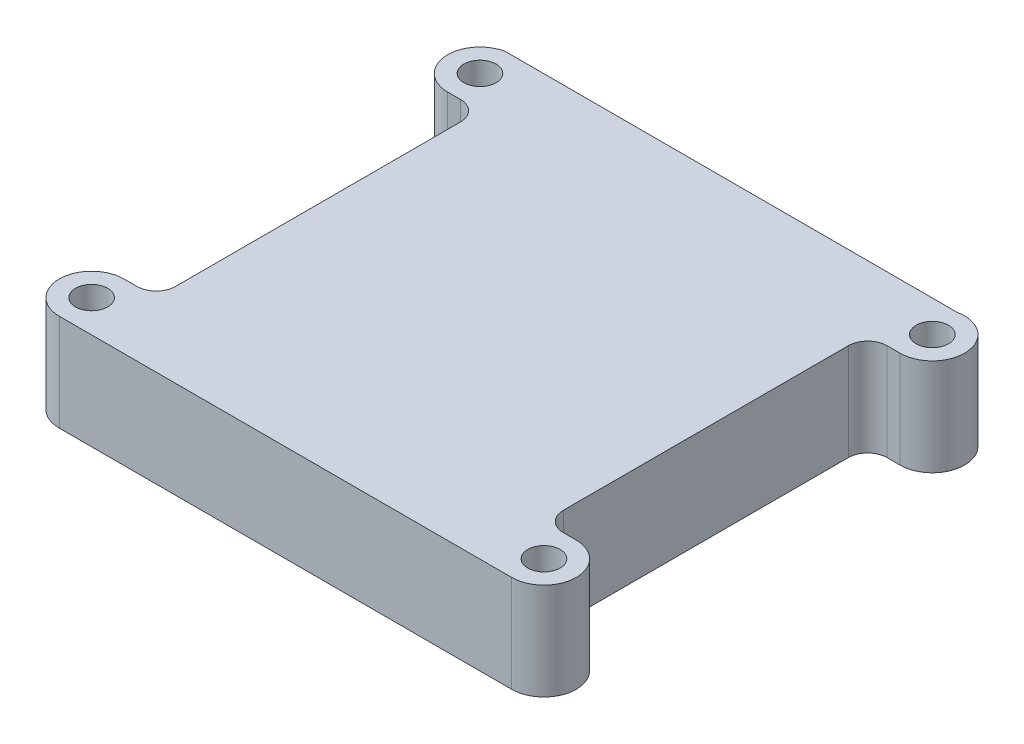
SolidWorks part; units mm, degrees
ref_plane "Front Plane" through (0, 0, 0) normal (0, 0, 1) x (1, 0, 0)
ref_plane "Top Plane" through (0, 0, 0) normal (0, 1, 0) x (1, 0, 0)
ref_plane "Right Plane" through (0, 0, 0) normal (1, 0, 0) x (0, 0, -1)
sketch "Sketch1" plane through (0, 0, 0) normal (0, 1, 0) x (1, 0, 0)
  line L0 (-35, 30.099) -> (35, 30.099) construction
  line L1 (-30, -35) -> (30, -35)
  line L2 (-30, -22) -> (-30, 22.099)
  line L3 (-30, 35) -> (30, 35)
  line L5 (-30, -35) -> (30, 35) construction
  line L6 (-30, 35) -> (30, -35) construction
  line L7 (-35.9898, 35) -> (-30, 35)
  line L8 (-35, 25.099) -> (-33, 25.099)
  line L9 (-35, -30) -> (35, -30) construction
  line L10 (-35, -25) -> (-33, -25)
  line L11 (-35, -35) -> (-30, -35)
  line L12 (33, 25.099) -> (35, 25.099)
  line L13 (30, 35) -> (34.0102, 35)
  line L14 (33, -25) -> (35, -25)
  line L15 (30, -35) -> (35, -35)
  line L16 (30, -22) -> (30, 22.099)
  arc A0 (-35.9898, 35) -> (-35, 25.099) centre (-35, 30.099) ccw
  arc A1 (35, 25.099) -> (34.0102, 35) centre (35, 30.099) ccw
  arc A2 (-35, -25) -> (-35, -35) centre (-35, -30) ccw
  arc A3 (35, -35) -> (35, -25) centre (35, -30) ccw
  circle A4 centre (-35, 30.099) radius 2.5
  circle A5 centre (35, 30.099) radius 2.5
  circle A6 centre (35, -30) radius 2.5
  circle A7 centre (-35, -30) radius 2.5
  arc A8 (33, 25.099) -> (30, 22.099) centre (33, 22.099) ccw
  arc A9 (33, -25) -> (30, -22) centre (33, -22) cw
  arc A10 (-33, -25) -> (-30, -22) centre (-33, -22) ccw
  arc A11 (-33, 25.099) -> (-30, 22.099) centre (-33, 22.099) cw
  point P0 (0, 0)
  point P8 (-0.9898, 28.4558)
  point P13 (0, -24.2219)
  dimension "D5" = 5
  dimension "D3" = 5
  dimension "D6" = 3
  dimension "D1" = 60
  dimension "D2" = 70
  dimension "D4" = 5
extrude "Boss-Extrude1" add sketch "Sketch1" along normal blind 15
